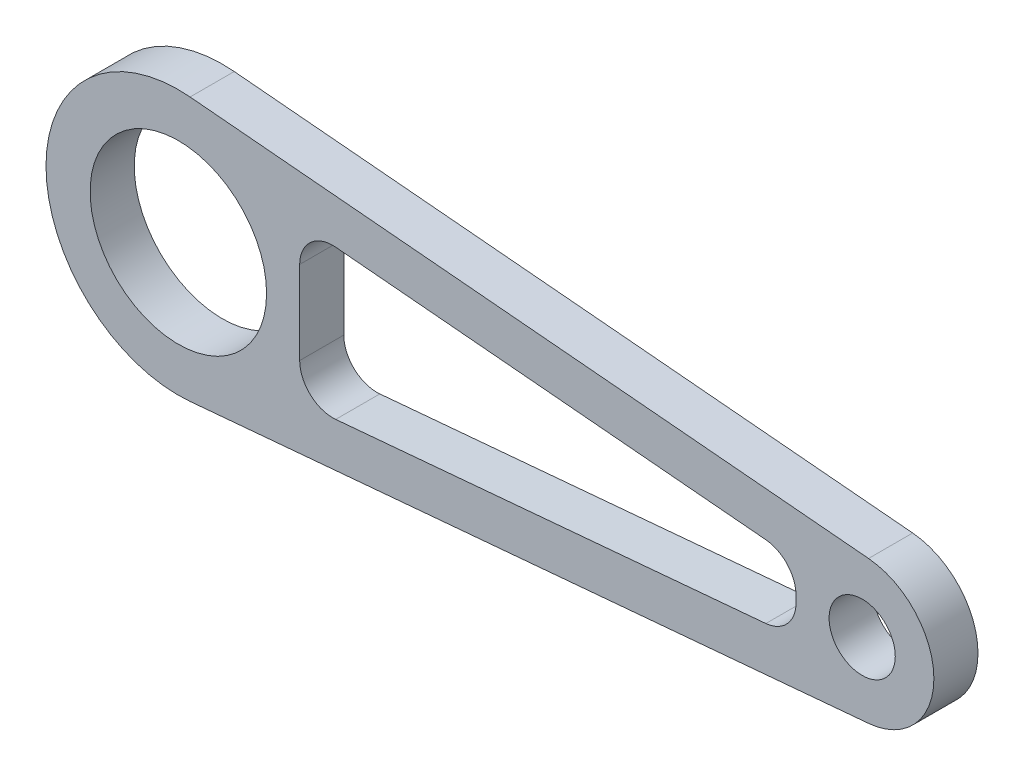
SolidWorks part; units mm, degrees
ref_plane "Plan1" through (0, 0, 0) normal (0, 0, 1) x (1, 0, 0)
ref_plane "Plan2" through (0, 0, 0) normal (0, 1, 0) x (1, 0, 0)
ref_plane "Plan3" through (0, 0, 0) normal (1, 0, 0) x (0, 0, -1)
sketch "Esquisse1" plane through (0, 0, 0) normal (0, 0, 1) x (1, 0, 0)
  line L0 (1.0645, 11.9527) -> (62.5766, 6.4744)
  line L1 (1.0645, -11.9527) -> (62.5766, -6.4744)
  line L2 (14.2661, 6.7611) -> (53.2661, 3.2877)
  line L3 (14.2661, -6.7611) -> (53.2661, -3.2877)
  line L4 (11, 3.7729) -> (11, -3.7729)
  line L5 (56, 0.2996) -> (56, -0.2996)
  arc A0 (1.0645, 11.9527) -> (1.0645, -11.9527) centre (0, 0) ccw
  arc A1 (62.5766, -6.4744) -> (62.5766, 6.4744) centre (62, 0) ccw
  circle A2 centre (0, 0) radius 8
  circle A3 centre (62, 0) radius 3
  arc A4 (53.2661, -3.2877) -> (56, -0.2996) centre (53, -0.2996) ccw
  arc A5 (11, -3.7729) -> (14.2661, -6.7611) centre (14, -3.7729) ccw
  arc A6 (11, 3.7729) -> (14.2661, 6.7611) centre (14, 3.7729) cw
  arc A7 (56, 0.2996) -> (53.2661, 3.2877) centre (53, 0.2996) ccw
  dimension "D1" = 24
  dimension "D2" = 13
  dimension "D4" = 16
  dimension "D5" = 6
  dimension "D9" = 3
  dimension "D3" = 62
  dimension "D7" = 45
  dimension "D8" = 11
  dimension "D6" = 4
extrude "Base-Extrusion" add sketch "Esquisse1" along normal mid plane 4
